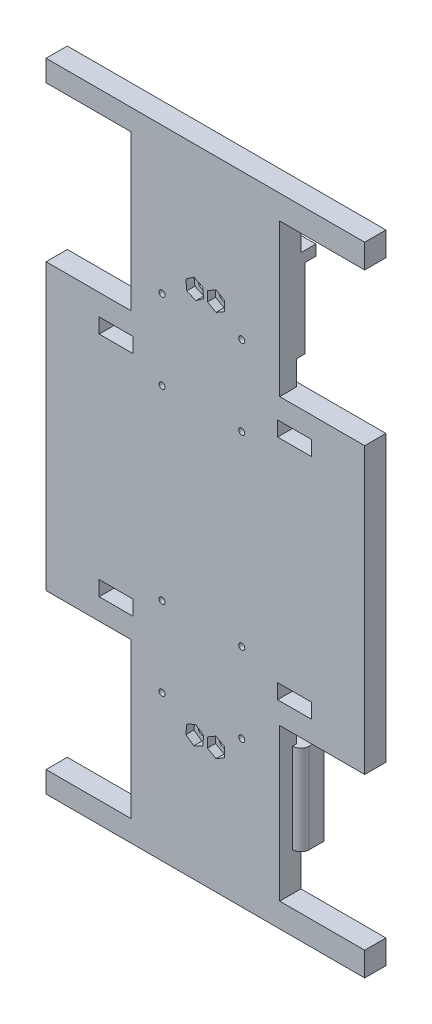
SolidWorks part; units mm, degrees
ref_plane "Front Plane" through (0, 0, 0) normal (0, 0, 1) x (1, 0, 0)
ref_plane "Top Plane" through (0, 0, 0) normal (0, 1, 0) x (1, 0, 0)
ref_plane "Right Plane" through (0, 0, 0) normal (1, 0, 0) x (0, 0, -1)
sketch "Sketch2" plane through (0, 0, 0) normal (0, 0, 1) x (1, 0, 0)
  line L0 (-180, 280) -> (-180, 200) construction
  line L1 (0, 0) -> (-150, 0)
  line L2 (0, 0) -> (0, 20)
  line L3 (0, 300) -> (-150, 300)
  line L4 (-150, 0) -> (-150, 20)
  line L5 (-180, 100) -> (-180, 20) construction
  line L6 (30, 280) -> (30, 200) construction
  line L7 (30, 100) -> (30, 20) construction
  line L8 (-180, 280) -> (-150, 280) construction
  line L9 (-180, 200) -> (-150, 200) construction
  line L10 (30, 280) -> (0, 280) construction
  line L11 (30, 200) -> (0, 200) construction
  line L12 (-180, 100) -> (-150, 100) construction
  line L13 (-180, 20) -> (-150, 20) construction
  line L14 (30, 100) -> (0, 100) construction
  line L15 (30, 20) -> (0, 20) construction
  line L16 (0, 280) -> (0, 300)
  line L17 (-150, 280) -> (-110, 280)
  line L19 (-150, 200) -> (-110, 200)
  line L20 (-110, 280) -> (-110, 200)
  line L21 (0, 280) -> (-40, 280)
  line L23 (0, 200) -> (-40, 200)
  line L24 (-40, 280) -> (-40, 200)
  line L25 (-150, 100) -> (-110, 100)
  line L27 (-150, 20) -> (-110, 20)
  line L28 (-110, 100) -> (-110, 20)
  line L29 (0, 100) -> (-40, 100)
  line L31 (0, 20) -> (-40, 20)
  line L32 (-40, 100) -> (-40, 20)
  line L33 (-150, 280) -> (-150, 300)
  line L34 (-150, 100) -> (-150, 200)
  line L35 (0, 100) -> (0, 200)
  dimension "D1" = 300
  dimension "D2" = 80
  dimension "D3" = 150
  dimension "D4" = 20
  dimension "D5" = 20
  dimension "D6" = 30
  dimension "D7" = 30
  dimension "D8" = 40
extrude "Boss-Extrude1" add sketch "Sketch2" along normal blind 10
sketch "Sketch3" plane through (0, 0, 0) normal (0, 0, -1) x (-1, 0, 0)
  line L0 (110, 20) -> (150, 20) construction
  line L5 (40, 100) -> (110, 100) construction
  line L22 (40, 100) -> (40, 85.9941) construction
  line L24 (40, 20) -> (110, 20) construction
  line L25 (110, 100) -> (110, 85.9941) construction
  line L29 (40, 60) -> (110, 60) construction
  line L30 (110, 34.6298) -> (110, 20) construction
  line L33 (40, 34.2339) -> (58.8, 34.2339)
  line L34 (58.8, 82.9565) -> (58.8, 34.2339)
  line L37 (110, 34.6298) -> (91.2, 34.6298)
  line L38 (91.2, 82.9565) -> (91.2, 34.6298)
  line L40 (40, 34.2339) -> (40, 29.2339)
  line L41 (40, 29.2339) -> (63.8, 29.2339)
  line L42 (63.8, 82.9565) -> (63.8, 29.2339)
  line L45 (110, 29.2339) -> (86.2, 29.2339)
  line L46 (86.2, 82.9565) -> (86.2, 29.2339)
  line L47 (110, 34.6298) -> (110, 29.2339)
  line L48 (58.8, 82.9565) -> (63.8, 82.9565)
  line L49 (91.2, 82.9565) -> (86.2, 82.9565)
  line L50 (40, 34.2339) -> (40, 20) construction
  line L51 (110, 100) -> (110, 20) construction
  dimension "D1" = 18.8
  dimension "D2" = 5
  dimension "D3" = 5
extrude "Boss-Extrude3" add sketch "Sketch3" along normal blind 7
sketch "Sketch4" plane through (0, 0, 0) normal (0, 0, -1) x (-1, 0, 0)
  line L1 (58.8, 82.9565) -> (40, 82.9565)
  line L2 (58.8, 82.9565) -> (58.8, 34.2339)
  line L3 (58.8, 34.2339) -> (40, 34.2339)
  line L4 (40, 82.9565) -> (40, 34.2339)
  line L5 (91.2, 82.9565) -> (110, 82.9565)
  line L6 (91.2, 82.9565) -> (91.2, 34.6298)
  line L7 (91.2, 34.6298) -> (110, 34.6298)
  line L8 (110, 82.9565) -> (110, 34.6298)
extrude "Boss-Extrude4" add sketch "Sketch4" along normal blind 2
sketch "Sketch5" plane through (0, 0, -2) normal (0, 0, -1) x (-1, 0, 0)
  line L0 (40, 82.9565) -> (40, 34.2339) construction
  line L1 (58.8, 82.9565) -> (40, 82.9565)
  line L2 (58.8, 82.9565) -> (58.8, 71.4798)
  line L3 (58.8, 71.4798) -> (40, 71.4798)
  line L4 (40, 82.9565) -> (40, 71.4798)
  line L5 (91.2, 34.6298) -> (91.2, 82.9565) construction
  line L6 (110, 82.9565) -> (91.2, 82.9565)
  line L7 (110, 82.9565) -> (110, 71.4798)
  line L8 (110, 71.4798) -> (91.2, 71.4798)
  line L9 (91.2, 82.9565) -> (91.2, 71.4798)
  dimension "D1" = 11.4766
sketch "Sketch6" plane through (0, 0, -7) normal (0, 0, -1) x (-1, 0, 0)
  line L0 (63.8, 29.2339) -> (63.8, 82.9565) construction
  line L1 (40, 82.9565) -> (55.1725, 82.9565)
  line L2 (40, 82.9565) -> (40, 71.4798)
  line L3 (40, 71.4798) -> (58.8, 71.4798)
  line L5 (91.2, 82.9565) -> (110, 82.9565)
  line L7 (95.4907, 71.4798) -> (110, 71.4798)
  line L8 (110, 82.9565) -> (110, 71.4798)
  line L9 (55.1725, 82.9565) -> (63.8, 82.9565)
  line L11 (58.8, 71.4798) -> (63.8, 71.4798)
  line L12 (63.8, 82.9565) -> (63.8, 71.4798)
  line L14 (86.2, 82.9565) -> (91.2, 82.9565)
  line L15 (86.2, 82.9565) -> (86.2, 71.4798)
  line L16 (86.2, 71.4798) -> (95.4907, 71.4798)
extrude "Cut-Extrude2" cut sketch "Sketch6" against normal blind 9
sketch "Sketch7" plane through (0, 0, 0) normal (0, 0, -1) x (-1, 0, 0)
  line L0 (40, 71.4798) -> (40, 34.2339) construction
  line L1 (150, 0) -> (0, 0) construction
  circle A0 centre (70, 59.0298) radius 2.165
  circle A1 centre (80, 59.0298) radius 2.165
  dimension "D4" = 4.33
  dimension "D1" = 30
  dimension "D2" = 10
  dimension "D3" = 59.0298
extrude "Cut-Extrude3" cut sketch "Sketch7" against normal through all
sketch "Sketch8" plane through (0, 0, 10) normal (0, 0, 1) x (1, 0, 0)
  line L1 (-83.7401, 61.7079) -> (-84.1893, 57.1299)
  line L2 (-84.1893, 57.1299) -> (-80.4492, 54.4518)
  line L3 (-80.4492, 54.4518) -> (-76.2599, 56.3518)
  line L4 (-76.2599, 56.3518) -> (-75.8107, 60.9298)
  line L5 (-75.8107, 60.9298) -> (-79.5508, 63.6078)
  line L6 (-79.5508, 63.6078) -> (-83.7401, 61.7079)
  line L7 (-70, 63.6298) -> (-73.9837, 61.3298)
  line L8 (-73.9837, 61.3298) -> (-73.9837, 56.7298)
  line L9 (-73.9837, 56.7298) -> (-70, 54.4298)
  line L10 (-70, 54.4298) -> (-66.0163, 56.7298)
  line L11 (-66.0163, 56.7298) -> (-66.0163, 61.3298)
  line L12 (-66.0163, 61.3298) -> (-70, 63.6298)
  circle A0 centre (-80, 59.0298) radius 3.9837 construction
  circle A1 centre (-70, 59.0298) radius 3.9837 construction
  dimension "D1" = 4.6
extrude "Cut-Extrude4" cut sketch "Sketch8" against normal blind 3.8
sketch "Sketch9" plane through (0, 29.2339, 0) normal (0, -1, 0) x (1, 0, 0)
  line L0 (-150, 0) -> (0, 0) construction
  line L1 (-110, -7) -> (-113.9, -7)
  line L2 (-110, -7) -> (-110, 0)
  line L4 (-113.9, -7) -> (-113.9, 0)
  line L5 (-110, 3.9) -> (-110, 0)
  line L6 (-40, -7) -> (-36.1, -7)
  line L7 (-40, -7) -> (-40, 0)
  line L9 (-36.1, -7) -> (-36.1, 0)
  line L12 (-40, 3.9) -> (-40, 0)
  arc A0 (-110, 3.9) -> (-113.9, 0) centre (-110, 0) ccw
  arc A2 (-36.1, 0) -> (-40, 3.9) centre (-40, 0) ccw
  dimension "D1" = 3.9
extrude "Boss-Extrude5" add sketch "Sketch9" against normal up to surface (42.2459 mm away) up to face at (-94.4286, 71.4798, -2)
ref_plane "Plane1" through (0, 150, 0) normal (0, 1, 0) x (1, 0, 0)
mirror "Mirror2" about plane through (0, 150, 0) normal (0, 1, 0) of "Cut-Extrude2", "Boss-Extrude3", "Boss-Extrude4"
mirror "Mirror3" about plane through (0, 150, 0) normal (0, 1, 0) of "Cut-Extrude3"
mirror "Mirror4" about plane through (0, 150, 0) normal (0, 1, 0) of "Cut-Extrude4"
sketch "Sketch10" plane through (0, 0, 0) normal (0, 0, -1) x (-1, 0, 0)
  line L2 (150, 300) -> (150, 280) construction
  line L3 (0, 288.6638) -> (40, 288.6638)
  line L4 (0, 288.6638) -> (0, 280)
  line L5 (0, 280) -> (40, 280)
  line L6 (40, 288.6638) -> (40, 280)
  line L7 (150, 290) -> (110, 290)
  line L8 (150, 290) -> (150, 280)
  line L9 (150, 280) -> (110, 280)
  line L10 (110, 290) -> (110, 280)
  dimension "D2" = 10
extrude "Cut-Extrude5" cut sketch "Sketch10" against normal through all
mirror "Mirror5" about plane through (0, 150, 0) normal (0, 1, 0) of "Cut-Extrude5"
sketch "Sketch11" plane through (0, 0, 0) normal (0, 0, -1) x (-1, 0, 0)
  line L0 (51.3081, 300) -> (51.3081, 254.1702) construction
  line L1 (0, 300) -> (150, 300) construction
  line L2 (110, 228.5202) -> (110, 217.0435) construction
  line L3 (0, 200) -> (40, 200)
  line L4 (0, 200) -> (0, 217.0435)
  line L5 (0, 217.0435) -> (40, 217.0435)
  line L6 (40, 200) -> (40, 217.0435)
  line L7 (110, 217.0435) -> (150, 217.0435)
  line L8 (110, 217.0435) -> (110, 200)
  line L9 (110, 200) -> (150, 200)
  line L10 (150, 217.0435) -> (150, 200)
  line L11 (0, 217.0435) -> (0, 262.8734) construction
  dimension "D1" = 45.8298
extrude "Boss-Extrude6" add sketch "Sketch11" against normal through all
mirror "Mirror6" about plane through (0, 150, 0) normal (0, 1, 0) of "Boss-Extrude6"
sketch "Sketch12" plane through (0, 0, 10) normal (0, 0, 1) x (1, 0, 0)
  line L0 (-150, 217.0435) -> (-110, 217.0435) construction
  line L1 (-125, 207.0435) -> (-109, 207.0435)
  line L2 (-125, 207.0435) -> (-125, 200.0435)
  line L3 (-125, 200.0435) -> (-109, 200.0435)
  line L4 (-109, 207.0435) -> (-109, 200.0435)
  line L5 (-25, 200.0435) -> (-41, 200.0435)
  line L6 (-25, 200.0435) -> (-25, 207.0435)
  line L7 (-25, 207.0435) -> (-41, 207.0435)
  line L8 (-41, 200.0435) -> (-41, 207.0435)
  line L9 (-125, 99.9565) -> (-109, 99.9565)
  line L10 (-125, 99.9565) -> (-125, 92.9565)
  line L11 (-125, 92.9565) -> (-109, 92.9565)
  line L12 (-109, 99.9565) -> (-109, 92.9565)
  line L13 (-41, 99.9565) -> (-25, 99.9565)
  line L14 (-41, 99.9565) -> (-41, 92.9565)
  line L15 (-41, 92.9565) -> (-25, 92.9565)
  line L16 (-25, 99.9565) -> (-25, 92.9565)
  line L17 (-150, 217.0435) -> (-150, 82.9565) construction
  line L18 (0, 82.9565) -> (0, 217.0435) construction
  line L19 (-150, 82.9565) -> (-110, 82.9565) construction
  dimension "D1" = 10
  dimension "D2" = 25
  dimension "D3" = 25
  dimension "D4" = 10
  dimension "D5" = 7
  dimension "D6" = 16
extrude "Cut-Extrude6" cut sketch "Sketch12" against normal up to next
hole_wizard "Ø1.5mm Dowel Hole1" positions "Sketch15" profile "Sketch16" hole size "Ø1.5" standard "ANSI Metric" end condition up to next
sketch "Sketch15" plane through (0, 0, 10) normal (0, 0, 1) x (1, 0, 0)
  point P0 (-57.8846, 231.3525)
  point P3 (-95.4024, 231.3525)
  point P6 (-95.4024, 193.8346)
  point P9 (-57.8846, 193.8346)
  point P12 (-95.4024, 68.6475)
  point P15 (-57.8846, 106.1654)
  point P18 (-57.8846, 68.6475)
  point P21 (-95.4024, 106.1654)
sketch "Sketch16" plane through (-57.8846, 231.3525, 10) normal (1, 0, 0) x (0, -1, 0)
  line L0 (0, 0) -> (0, 12)
  line L1 (0, 12) -> (1.425, 12)
  line L2 (1.425, 12) -> (1.425, 0)
  line L5 (1.425, 0) -> (0, 0)
  line L11 (0, -6.35) -> (0, 107.95) construction
  dimension "Thru Hole Dia." = 2.85
  dimension "Thru Hole Depth" = 12
